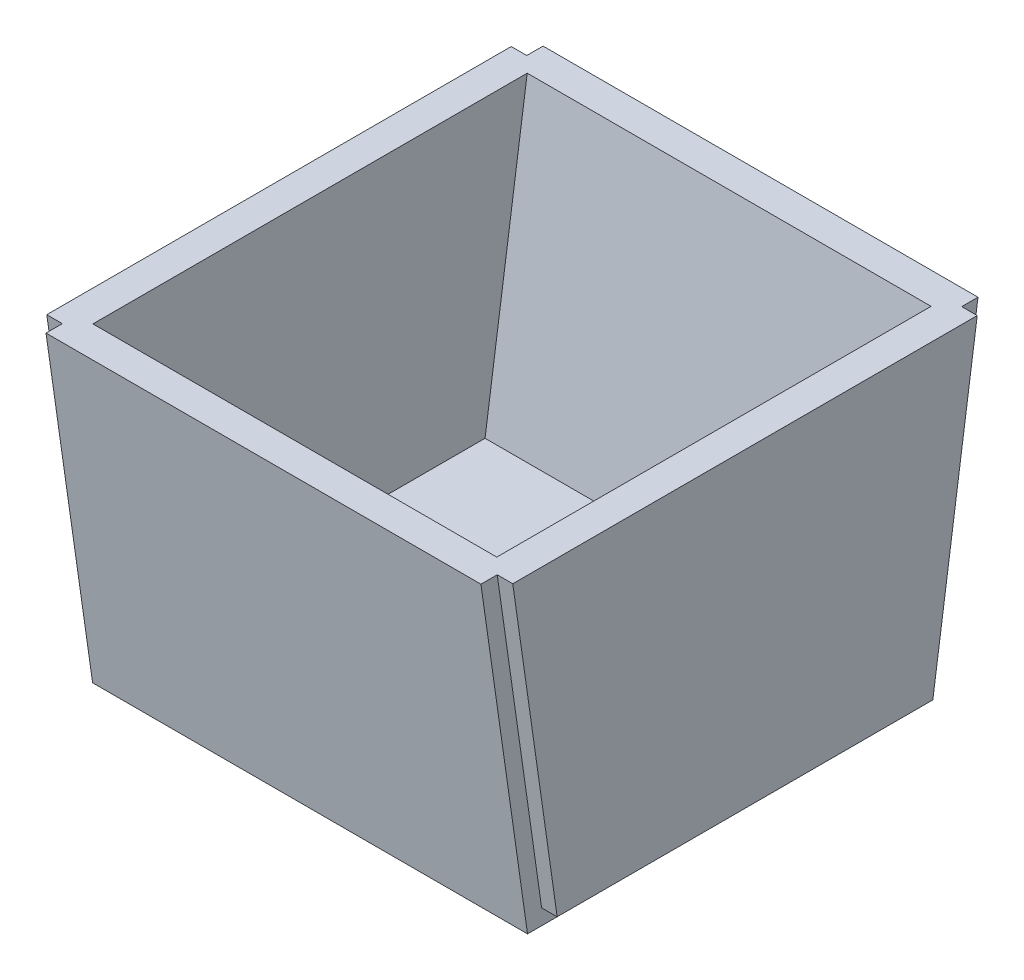
SolidWorks part; units mm, degrees
ref_plane "Front Plane" through (0, 0, 0) normal (0, 0, 1) x (1, 0, 0)
ref_plane "Top Plane" through (0, 0, 0) normal (0, 1, 0) x (1, 0, 0)
ref_plane "Right Plane" through (0, 0, 0) normal (1, 0, 0) x (0, 0, -1)
sketch "Sketch1" plane through (0, 0, 0) normal (0, 1, 0) x (1, 0, 0)
  line L1 (-177.8, 165.1) -> (177.8, 165.1)
  line L2 (-177.8, 165.1) -> (-177.8, -165.1)
  line L3 (-177.8, -165.1) -> (177.8, -165.1)
  line L4 (177.8, 165.1) -> (177.8, -165.1)
  line L5 (-177.8, 165.1) -> (177.8, -165.1) construction
  line L6 (-177.8, -165.1) -> (177.8, 165.1) construction
  point P0 (0, 0)
  dimension "D1" = 355.6
  dimension "D2" = 330.2
ref_plane "Plane1" through (0, 266.7, 0) normal (0, 1, 0) x (1, 0, 0)
sketch "Sketch2" plane through (0, 266.7, 0) normal (0, 1, 0) x (1, 0, 0)
  line L1 (-177.8, 203.2) -> (177.8, 203.2)
  line L2 (-177.8, 203.2) -> (-177.8, -203.2)
  line L3 (-177.8, -203.2) -> (177.8, -203.2)
  line L4 (177.8, 203.2) -> (177.8, -203.2)
  line L5 (-177.8, 203.2) -> (177.8, -203.2) construction
  line L6 (-177.8, -203.2) -> (177.8, 203.2) construction
  point P0 (0, 0)
  dimension "D1" = 406.4
  dimension "D2" = 355.6
loft "Loft1" add profiles "Sketch1", "Sketch2"
shell "Shell1" thickness 25.4
sketch "Sketch4" plane through (177.8, 0, 0) normal (1, 0, 0) x (0, 0, -1)
  line L0 (189.865, 266.7) -> (153.5793, 12.7)
  line L4 (-153.5793, 12.7) -> (-189.865, 266.7)
  line L6 (-189.865, 266.7) -> (189.865, 266.7)
  line L7 (-153.5793, 12.7) -> (153.5793, 12.7)
  line L8 (-143.0707, 25.4) -> (143.0707, 25.4) construction
  line L9 (-165.1, 0) -> (-203.2, 266.7) construction
  line L10 (165.1, 0) -> (203.2, 266.7) construction
  line L11 (0, 240.3391) -> (0, 290.6385) construction
  line L12 (-203.2, 266.7) -> (203.2, 266.7) construction
  dimension "D1" = 12.7
  dimension "D2" = 379.73
extrude "Boss-Extrude2" add sketch "Sketch4" along normal blind 25.4 from surface at -12.7 starting at face at (165.1, 146.05, 0)
sketch "Sketch5" plane through (-177.8, 0, 0) normal (-1, 0, 0) x (0, 0, 1)
  line L4 (-153.5793, 12.7) -> (153.5793, 12.7)
  line L5 (-189.865, 266.7) -> (-153.5793, 12.7)
  line L6 (189.865, 266.7) -> (-189.865, 266.7)
  line L7 (153.5793, 12.7) -> (189.865, 266.7)
  line L8 (-153.5793, 12.7) -> (153.5793, 12.7)
  line L9 (-189.865, 266.7) -> (-153.5793, 12.7)
  line L10 (189.865, 266.7) -> (-189.865, 266.7)
  line L11 (153.5793, 12.7) -> (189.865, 266.7)
  dimension "D1" = 0
extrude "Boss-Extrude3" add sketch "Sketch5" along normal blind 12.7
